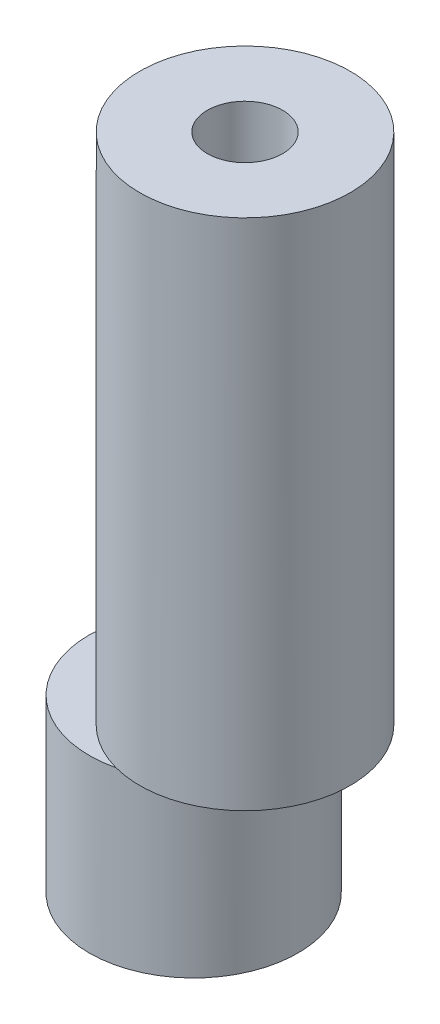
SolidWorks part; units mm, degrees
ref_plane "Front Plane" through (0, 0, 0) normal (0, 0, 1) x (1, 0, 0)
ref_plane "Top Plane" through (0, 0, 0) normal (0, 1, 0) x (1, 0, 0)
ref_plane "Right Plane" through (0, 0, 0) normal (1, 0, 0) x (0, 0, -1)
sketch "Sketch1" plane through (0, 0, 0) normal (0, 1, 0) x (1, 0, 0)
  circle A0 centre (0, 0) radius 3.05
  dimension "D1" = 6.1
extrude "Boss-Extrude1" add sketch "Sketch1" along normal blind 5
sketch "Sketch2" plane through (0, 5, 0) normal (0, 1, 0) x (1, 0, 0)
  line L0 (0, 0) -> (1.5, 0) construction
  circle A0 centre (1.5, 0) radius 3.075
  circle A1 centre (1.5, 0) radius 1.1
  dimension "D2" = 6.15
  dimension "D3" = 2.2
  dimension "D1" = 1.5
extrude "Boss-Extrude2" add sketch "Sketch2" along normal blind 15
sketch "Sketch3" plane through (0, 0, 0) normal (0, -1, 0) x (1, 0, 0)
  arc A0 (0.699, -2.9688) -> (0.699, 2.9688) centre (1.5, 0) ccw construction
  arc A1 (0.699, 2.9688) -> (0.699, -2.9688) centre (1.5, 0) ccw construction
  arc A2 (0.699, -2.9688) -> (0.699, 2.9688) centre (1.5, 0) ccw
  arc A3 (0.699, 2.9688) -> (0.699, -2.9688) centre (1.5, 0) ccw
